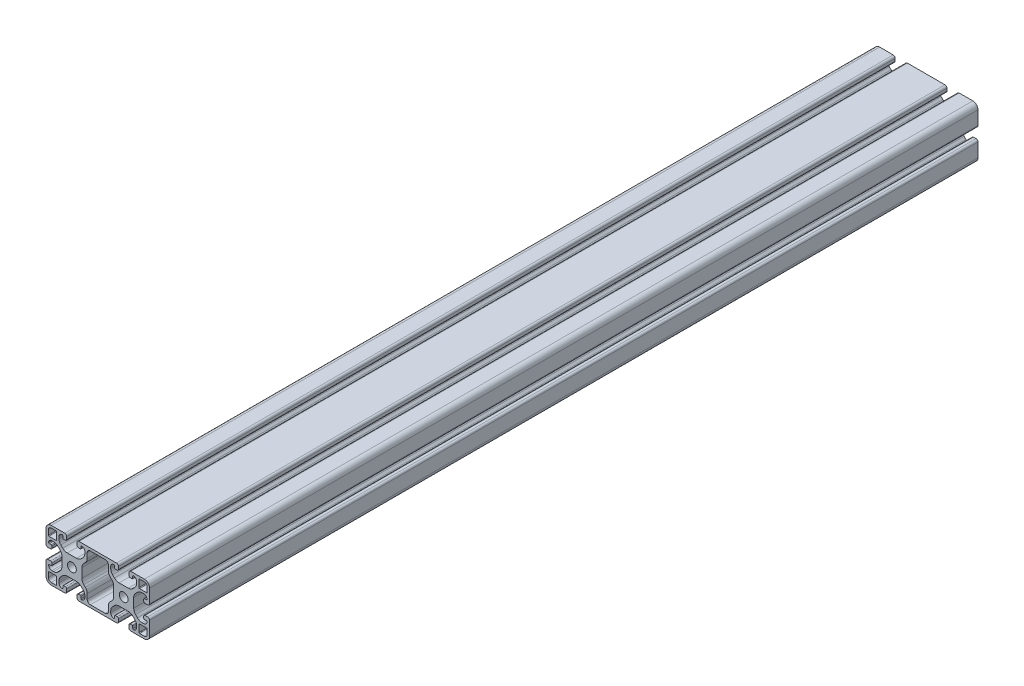
SolidWorks part; units mm, degrees
ref_plane "Plan de face" through (0, 0, 0) normal (0, 0, 1) x (1, 0, 0)
ref_plane "Plan de dessus" through (0, 0, 0) normal (0, 1, 0) x (1, 0, 0)
ref_plane "Plan de droite" through (0, 0, 0) normal (1, 0, 0) x (0, 0, -1)
ref_plane "Plan1" through (0, 0, 20) normal (0, 0, 1) x (1, 0, 0)
sketch "Esquisse1" plane through (0, 0, 20) normal (0, 0, 1) x (1, 0, 0)
  line L0 (66.5, 4.5) -> (65, 4.5)
  line L1 (64, 3.5) -> (64, 1.5)
  line L2 (65.5, 0) -> (76, 0)
  line L3 (80, 4) -> (80, 14.5)
  line L4 (78.5, 16) -> (76.5, 16)
  line L5 (75.5, 15) -> (75.5, 13.5)
  line L6 (76, 13) -> (77.5, 13)
  line L7 (75.5, 10) -> (74.1924, 10)
  line L8 (70.6569, 11.4645) -> (69.2145, 12.9069)
  line L9 (67.75, 16.4424) -> (67.75, 23.5576)
  line L10 (69.2145, 27.0931) -> (70.6569, 28.5355)
  line L11 (74.1924, 30) -> (75.5, 30)
  line L12 (77.5, 27) -> (76, 27)
  line L13 (75.5, 26.5) -> (75.5, 25)
  line L14 (76.5, 24) -> (78.5, 24)
  line L15 (80, 25.5) -> (80, 36)
  line L16 (76, 40) -> (65.5, 40)
  line L17 (64, 38.5) -> (64, 36.5)
  line L18 (65, 35.5) -> (66.5, 35.5)
  line L19 (67, 36) -> (67, 37.5)
  line L20 (70, 35.5) -> (70, 34.1924)
  line L21 (68.5355, 30.6569) -> (67.0931, 29.2145)
  line L22 (63.5576, 27.75) -> (56.4424, 27.75)
  line L23 (52.9069, 29.2145) -> (51.4645, 30.6569)
  line L24 (50, 34.1924) -> (50, 35.5)
  line L25 (53, 37.5) -> (53, 36)
  line L26 (53.5, 35.5) -> (55, 35.5)
  line L27 (56, 36.5) -> (56, 38.5)
  line L28 (54.5, 40) -> (25.5, 40)
  line L29 (24, 38.5) -> (24, 36.5)
  line L30 (25, 35.5) -> (26.5, 35.5)
  line L31 (27, 36) -> (27, 37.5)
  line L32 (30, 35.5) -> (30, 34.1924)
  line L33 (28.5355, 30.6569) -> (27.0931, 29.2145)
  line L34 (23.5576, 27.75) -> (16.4424, 27.75)
  line L35 (12.9069, 29.2145) -> (11.4645, 30.6569)
  line L36 (10, 34.1924) -> (10, 35.5)
  line L37 (13, 37.5) -> (13, 36)
  line L38 (13.5, 35.5) -> (15, 35.5)
  line L39 (16, 36.5) -> (16, 38.5)
  line L40 (14.5, 40) -> (4, 40)
  line L41 (0, 36) -> (0, 25.5)
  line L42 (1.5, 24) -> (3.5, 24)
  line L43 (4.5, 25) -> (4.5, 26.5)
  line L44 (4, 27) -> (2.5, 27)
  line L45 (4.5, 30) -> (5.8076, 30)
  line L46 (9.3431, 28.5355) -> (10.7855, 27.0931)
  line L47 (12.25, 23.5576) -> (12.25, 16.4424)
  line L48 (10.7855, 12.9069) -> (9.3431, 11.4645)
  line L49 (5.8076, 10) -> (4.5, 10)
  line L50 (2.5, 13) -> (4, 13)
  line L51 (4.5, 13.5) -> (4.5, 15)
  line L52 (3.5, 16) -> (1.5, 16)
  line L53 (0, 14.5) -> (0, 4)
  line L54 (4, 0) -> (14.5, 0)
  line L55 (16, 1.5) -> (16, 3.5)
  line L56 (15, 4.5) -> (13.5, 4.5)
  line L57 (13, 4) -> (13, 2.5)
  line L58 (10, 4.5) -> (10, 5.8076)
  line L59 (11.4645, 9.3431) -> (12.9069, 10.7855)
  line L60 (16.4424, 12.25) -> (23.5576, 12.25)
  line L61 (27.0931, 10.7855) -> (28.5355, 9.3431)
  line L62 (30, 5.8076) -> (30, 4.5)
  line L63 (27, 2.5) -> (27, 4)
  line L64 (26.5, 4.5) -> (25, 4.5)
  line L65 (24, 3.5) -> (24, 1.5)
  line L66 (25.5, 0) -> (54.5, 0)
  line L67 (56, 1.5) -> (56, 3.5)
  line L68 (55, 4.5) -> (53.5, 4.5)
  line L69 (53, 4) -> (53, 2.5)
  line L70 (50, 4.5) -> (50, 5.8076)
  line L71 (51.4645, 9.3431) -> (52.9069, 10.7855)
  line L72 (56.4424, 12.25) -> (63.5576, 12.25)
  line L73 (67.0931, 10.7855) -> (68.5355, 9.3431)
  line L74 (70, 5.8076) -> (70, 4.5)
  line L75 (67, 2.5) -> (67, 4)
  line L76 (31.8, 4.5) -> (31.8, 8.2503)
  line L77 (30.3355, 11.7858) -> (29.2145, 12.9069)
  line L78 (27.75, 16.4424) -> (27.75, 23.5576)
  line L79 (29.2145, 27.0931) -> (30.3355, 28.2142)
  line L80 (31.8, 31.7497) -> (31.8, 35.5)
  line L81 (34.3, 38) -> (45.7, 38)
  line L82 (48.2, 35.5) -> (48.2, 31.7497)
  line L83 (49.6645, 28.2142) -> (50.7855, 27.0931)
  line L84 (52.25, 23.5576) -> (52.25, 16.4424)
  line L85 (50.7855, 12.9069) -> (49.6645, 11.7858)
  line L86 (48.2, 8.2503) -> (48.2, 4.5)
  line L87 (45.7, 2) -> (34.3, 2)
  line L88 (7.7, 1.8) -> (4, 1.8)
  line L89 (1.8, 4) -> (1.8, 7.7)
  line L90 (2.3, 8.2) -> (7.7, 8.2)
  line L91 (8.2, 7.7) -> (8.2, 2.3)
  line L92 (72.3, 38.2) -> (76, 38.2)
  line L93 (78.2, 36) -> (78.2, 32.3)
  line L94 (77.7, 31.8) -> (72.3, 31.8)
  line L95 (71.8, 32.3) -> (71.8, 37.7)
  line L96 (78.2, 7.7) -> (78.2, 4)
  line L97 (76, 1.8) -> (72.3, 1.8)
  line L98 (71.8, 2.3) -> (71.8, 7.7)
  line L99 (72.3, 8.2) -> (77.7, 8.2)
  line L100 (1.8, 32.3) -> (1.8, 36)
  line L101 (4, 38.2) -> (7.7, 38.2)
  line L102 (8.2, 37.7) -> (8.2, 32.3)
  line L103 (7.7, 31.8) -> (2.3, 31.8)
  arc A0 (67, 4) -> (66.5, 4.5) centre (66.5, 4) ccw
  arc A1 (65, 4.5) -> (64, 3.5) centre (65, 3.5) ccw
  arc A2 (64, 1.5) -> (65.5, 0) centre (65.5, 1.5) ccw
  arc A3 (76, 0) -> (80, 4) centre (76, 4) ccw
  arc A4 (80, 14.5) -> (78.5, 16) centre (78.5, 14.5) ccw
  arc A5 (76.5, 16) -> (75.5, 15) centre (76.5, 15) ccw
  arc A6 (75.5, 13.5) -> (76, 13) centre (76, 13.5) ccw
  arc A7 (77.5, 13) -> (78, 12.5) centre (77.5, 12.5) cw
  arc A8 (78, 12.5) -> (75.5, 10) centre (75.5, 12.5) cw
  arc A9 (74.1924, 10) -> (70.6569, 11.4645) centre (74.1924, 15) cw
  arc A10 (69.2145, 12.9069) -> (67.75, 16.4424) centre (72.75, 16.4424) cw
  arc A11 (67.75, 23.5576) -> (69.2145, 27.0931) centre (72.75, 23.5576) cw
  arc A12 (70.6569, 28.5355) -> (74.1924, 30) centre (74.1924, 25) cw
  arc A13 (75.5, 30) -> (78, 27.5) centre (75.5, 27.5) cw
  arc A14 (78, 27.5) -> (77.5, 27) centre (77.5, 27.5) cw
  arc A15 (76, 27) -> (75.5, 26.5) centre (76, 26.5) ccw
  arc A16 (75.5, 25) -> (76.5, 24) centre (76.5, 25) ccw
  arc A17 (78.5, 24) -> (80, 25.5) centre (78.5, 25.5) ccw
  arc A18 (80, 36) -> (76, 40) centre (76, 36) ccw
  arc A19 (65.5, 40) -> (64, 38.5) centre (65.5, 38.5) ccw
  arc A20 (64, 36.5) -> (65, 35.5) centre (65, 36.5) ccw
  arc A21 (66.5, 35.5) -> (67, 36) centre (66.5, 36) ccw
  arc A22 (67, 37.5) -> (67.5, 38) centre (67.5, 37.5) cw
  arc A23 (67.5, 38) -> (70, 35.5) centre (67.5, 35.5) cw
  arc A24 (70, 34.1924) -> (68.5355, 30.6569) centre (65, 34.1924) cw
  arc A25 (67.0931, 29.2145) -> (63.5576, 27.75) centre (63.5576, 32.75) cw
  arc A26 (56.4424, 27.75) -> (52.9069, 29.2145) centre (56.4424, 32.75) cw
  arc A27 (51.4645, 30.6569) -> (50, 34.1924) centre (55, 34.1924) cw
  arc A28 (50, 35.5) -> (52.5, 38) centre (52.5, 35.5) cw
  arc A29 (52.5, 38) -> (53, 37.5) centre (52.5, 37.5) cw
  arc A30 (53, 36) -> (53.5, 35.5) centre (53.5, 36) ccw
  arc A31 (55, 35.5) -> (56, 36.5) centre (55, 36.5) ccw
  arc A32 (56, 38.5) -> (54.5, 40) centre (54.5, 38.5) ccw
  arc A33 (25.5, 40) -> (24, 38.5) centre (25.5, 38.5) ccw
  arc A34 (24, 36.5) -> (25, 35.5) centre (25, 36.5) ccw
  arc A35 (26.5, 35.5) -> (27, 36) centre (26.5, 36) ccw
  arc A36 (27, 37.5) -> (27.5, 38) centre (27.5, 37.5) cw
  arc A37 (27.5, 38) -> (30, 35.5) centre (27.5, 35.5) cw
  arc A38 (30, 34.1924) -> (28.5355, 30.6569) centre (25, 34.1924) cw
  arc A39 (27.0931, 29.2145) -> (23.5576, 27.75) centre (23.5576, 32.75) cw
  arc A40 (16.4424, 27.75) -> (12.9069, 29.2145) centre (16.4424, 32.75) cw
  arc A41 (11.4645, 30.6569) -> (10, 34.1924) centre (15, 34.1924) cw
  arc A42 (10, 35.5) -> (12.5, 38) centre (12.5, 35.5) cw
  arc A43 (12.5, 38) -> (13, 37.5) centre (12.5, 37.5) cw
  arc A44 (13, 36) -> (13.5, 35.5) centre (13.5, 36) ccw
  arc A45 (15, 35.5) -> (16, 36.5) centre (15, 36.5) ccw
  arc A46 (16, 38.5) -> (14.5, 40) centre (14.5, 38.5) ccw
  arc A47 (4, 40) -> (0, 36) centre (4, 36) ccw
  arc A48 (0, 25.5) -> (1.5, 24) centre (1.5, 25.5) ccw
  arc A49 (3.5, 24) -> (4.5, 25) centre (3.5, 25) ccw
  arc A50 (4.5, 26.5) -> (4, 27) centre (4, 26.5) ccw
  arc A51 (2.5, 27) -> (2, 27.5) centre (2.5, 27.5) cw
  arc A52 (2, 27.5) -> (4.5, 30) centre (4.5, 27.5) cw
  arc A53 (5.8076, 30) -> (9.3431, 28.5355) centre (5.8076, 25) cw
  arc A54 (10.7855, 27.0931) -> (12.25, 23.5576) centre (7.25, 23.5576) cw
  arc A55 (12.25, 16.4424) -> (10.7855, 12.9069) centre (7.25, 16.4424) cw
  arc A56 (9.3431, 11.4645) -> (5.8076, 10) centre (5.8076, 15) cw
  arc A57 (4.5, 10) -> (2, 12.5) centre (4.5, 12.5) cw
  arc A58 (2, 12.5) -> (2.5, 13) centre (2.5, 12.5) cw
  arc A59 (4, 13) -> (4.5, 13.5) centre (4, 13.5) ccw
  arc A60 (4.5, 15) -> (3.5, 16) centre (3.5, 15) ccw
  arc A61 (1.5, 16) -> (0, 14.5) centre (1.5, 14.5) ccw
  arc A62 (0, 4) -> (4, 0) centre (4, 4) ccw
  arc A63 (14.5, 0) -> (16, 1.5) centre (14.5, 1.5) ccw
  arc A64 (16, 3.5) -> (15, 4.5) centre (15, 3.5) ccw
  arc A65 (13.5, 4.5) -> (13, 4) centre (13.5, 4) ccw
  arc A66 (13, 2.5) -> (12.5, 2) centre (12.5, 2.5) cw
  arc A67 (12.5, 2) -> (10, 4.5) centre (12.5, 4.5) cw
  arc A68 (10, 5.8076) -> (11.4645, 9.3431) centre (15, 5.8076) cw
  arc A69 (12.9069, 10.7855) -> (16.4424, 12.25) centre (16.4424, 7.25) cw
  arc A70 (23.5576, 12.25) -> (27.0931, 10.7855) centre (23.5576, 7.25) cw
  arc A71 (28.5355, 9.3431) -> (30, 5.8076) centre (25, 5.8076) cw
  arc A72 (30, 4.5) -> (27.5, 2) centre (27.5, 4.5) cw
  arc A73 (27.5, 2) -> (27, 2.5) centre (27.5, 2.5) cw
  arc A74 (27, 4) -> (26.5, 4.5) centre (26.5, 4) ccw
  arc A75 (25, 4.5) -> (24, 3.5) centre (25, 3.5) ccw
  arc A76 (24, 1.5) -> (25.5, 0) centre (25.5, 1.5) ccw
  arc A77 (54.5, 0) -> (56, 1.5) centre (54.5, 1.5) ccw
  arc A78 (56, 3.5) -> (55, 4.5) centre (55, 3.5) ccw
  arc A79 (53.5, 4.5) -> (53, 4) centre (53.5, 4) ccw
  arc A80 (53, 2.5) -> (52.5, 2) centre (52.5, 2.5) cw
  arc A81 (52.5, 2) -> (50, 4.5) centre (52.5, 4.5) cw
  arc A82 (50, 5.8076) -> (51.4645, 9.3431) centre (55, 5.8076) cw
  arc A83 (52.9069, 10.7855) -> (56.4424, 12.25) centre (56.4424, 7.25) cw
  arc A84 (63.5576, 12.25) -> (67.0931, 10.7855) centre (63.5576, 7.25) cw
  arc A85 (68.5355, 9.3431) -> (70, 5.8076) centre (65, 5.8076) cw
  arc A86 (70, 4.5) -> (67.5, 2) centre (67.5, 4.5) cw
  arc A87 (67.5, 2) -> (67, 2.5) centre (67.5, 2.5) cw
  circle A88 centre (20, 20) radius 3.4
  circle A89 centre (60, 20) radius 3.4
  arc A90 (34.3, 2) -> (31.8, 4.5) centre (34.3, 4.5) cw
  arc A91 (31.8, 8.2503) -> (30.3355, 11.7858) centre (26.8, 8.2503) ccw
  arc A92 (29.2145, 12.9069) -> (27.75, 16.4424) centre (32.75, 16.4424) cw
  arc A93 (27.75, 23.5576) -> (29.2145, 27.0931) centre (32.75, 23.5576) cw
  arc A94 (30.3355, 28.2142) -> (31.8, 31.7497) centre (26.8, 31.7497) ccw
  arc A95 (31.8, 35.5) -> (34.3, 38) centre (34.3, 35.5) cw
  arc A96 (45.7, 38) -> (48.2, 35.5) centre (45.7, 35.5) cw
  arc A97 (48.2, 31.7497) -> (49.6645, 28.2142) centre (53.2, 31.7497) ccw
  arc A98 (50.7855, 27.0931) -> (52.25, 23.5576) centre (47.25, 23.5576) cw
  arc A99 (52.25, 16.4424) -> (50.7855, 12.9069) centre (47.25, 16.4424) cw
  arc A100 (49.6645, 11.7858) -> (48.2, 8.2503) centre (53.2, 8.2503) ccw
  arc A101 (48.2, 4.5) -> (45.7, 2) centre (45.7, 4.5) cw
  arc A102 (8.2, 2.3) -> (7.7, 1.8) centre (7.7, 2.3) cw
  arc A103 (4, 1.8) -> (1.8, 4) centre (4, 4) cw
  arc A104 (1.8, 7.7) -> (2.3, 8.2) centre (2.3, 7.7) cw
  arc A105 (7.7, 8.2) -> (8.2, 7.7) centre (7.7, 7.7) cw
  arc A106 (71.8, 37.7) -> (72.3, 38.2) centre (72.3, 37.7) cw
  arc A107 (76, 38.2) -> (78.2, 36) centre (76, 36) cw
  arc A108 (78.2, 32.3) -> (77.7, 31.8) centre (77.7, 32.3) cw
  arc A109 (72.3, 31.8) -> (71.8, 32.3) centre (72.3, 32.3) cw
  arc A110 (77.7, 8.2) -> (78.2, 7.7) centre (77.7, 7.7) cw
  arc A111 (78.2, 4) -> (76, 1.8) centre (76, 4) cw
  arc A112 (72.3, 1.8) -> (71.8, 2.3) centre (72.3, 2.3) cw
  arc A113 (71.8, 7.7) -> (72.3, 8.2) centre (72.3, 7.7) cw
  arc A114 (2.3, 31.8) -> (1.8, 32.3) centre (2.3, 32.3) cw
  arc A115 (1.8, 36) -> (4, 38.2) centre (4, 36) cw
  arc A116 (7.7, 38.2) -> (8.2, 37.7) centre (7.7, 37.7) cw
  arc A117 (8.2, 32.3) -> (7.7, 31.8) centre (7.7, 32.3) cw
extrude "Boss.-Extru.1" add sketch "Esquisse1" against normal blind 640
